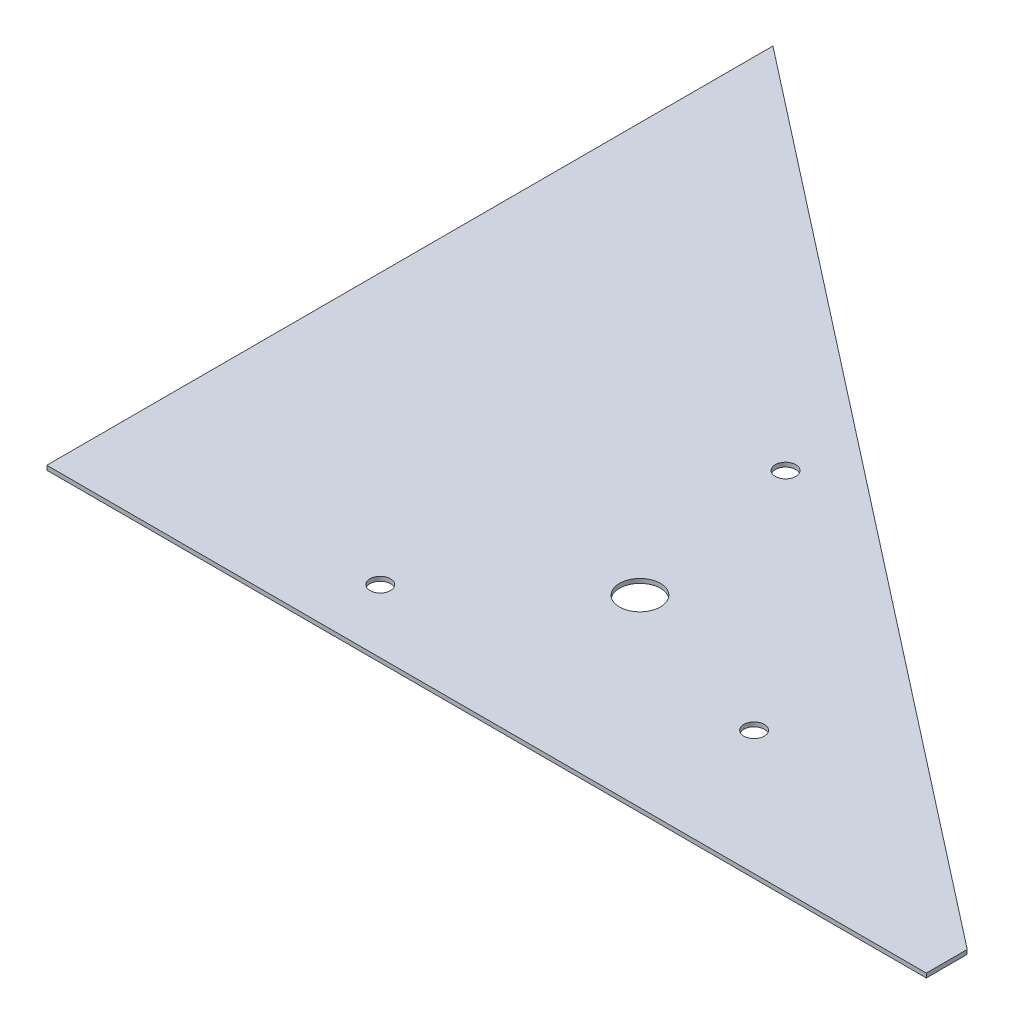
SolidWorks part; units mm, degrees
ref_plane "Front Plane" through (0, 0, 0) normal (0, 0, 1) x (1, 0, 0)
ref_plane "Top Plane" through (0, 0, 0) normal (0, 1, 0) x (1, 0, 0)
ref_plane "Right Plane" through (0, 0, 0) normal (1, 0, 0) x (0, 0, -1)
sketch "Sketch1" plane through (0, 0, 0) normal (0, 1, 0) x (1, 0, 0)
  line L0 (0, 450.85) -> (0, 0)
  line L1 (0, 0) -> (546.1, 0)
  line L2 (546.1, 0) -> (546.1, 25.4)
  line L3 (546.1, 25.4) -> (0, 450.85)
  dimension "D1" = 450.85
  dimension "D2" = 546.1
  dimension "D3" = 25.4
extrude "Boss-Extrude1" add sketch "Sketch1" along normal blind 2.6568
ref_plane "Plane1" through (220.1389, 0, -282.5663) normal (0.6146, 0, -0.7889) x (-0.7889, 0, -0.6146)
sketch "Sketch2" plane through (0, 0, 0) normal (0, -1, 0) x (1, 0, 0)
  line L0 (546.1, 0) -> (546.1, -25.4) construction
  line L1 (0, 0) -> (546.1, 0) construction
  circle A0 centre (254, -114.3) radius 12.7
  dimension "D1" = 25.4
  dimension "D2" = 292.1
  dimension "D3" = 114.3
extrude "Cut-Extrude1" cut sketch "Sketch2" against normal through all
sketch "Sketch3" plane through (0, 2.6568, 0) normal (0, 1, 0) x (1, 0, 0)
  line L0 (254, 228.6) -> (254, 0) construction
  line L1 (139.7, 114.3) -> (368.3, 114.3) construction
  line L2 (254, 114.3) -> (529.4177, 19.4661) construction
  circle A0 centre (254, 114.3) radius 101.6 construction
  circle A1 centre (254, 114.3) radius 114.3 construction
  circle A2 centre (362.0728, 77.0876) radius 6.35
  circle A3 centre (167.7367, 39.3125) radius 6.35
  circle A4 centre (232.1905, 226.5) radius 6.35
  point P18 (254, 114.3)
  dimension "D1" = 203.2
  dimension "D2" = 228.6
  dimension "D4" = 12.7
  dimension "D3" = 19
extrude "Cut-Extrude2" cut sketch "Sketch3" against normal through all
